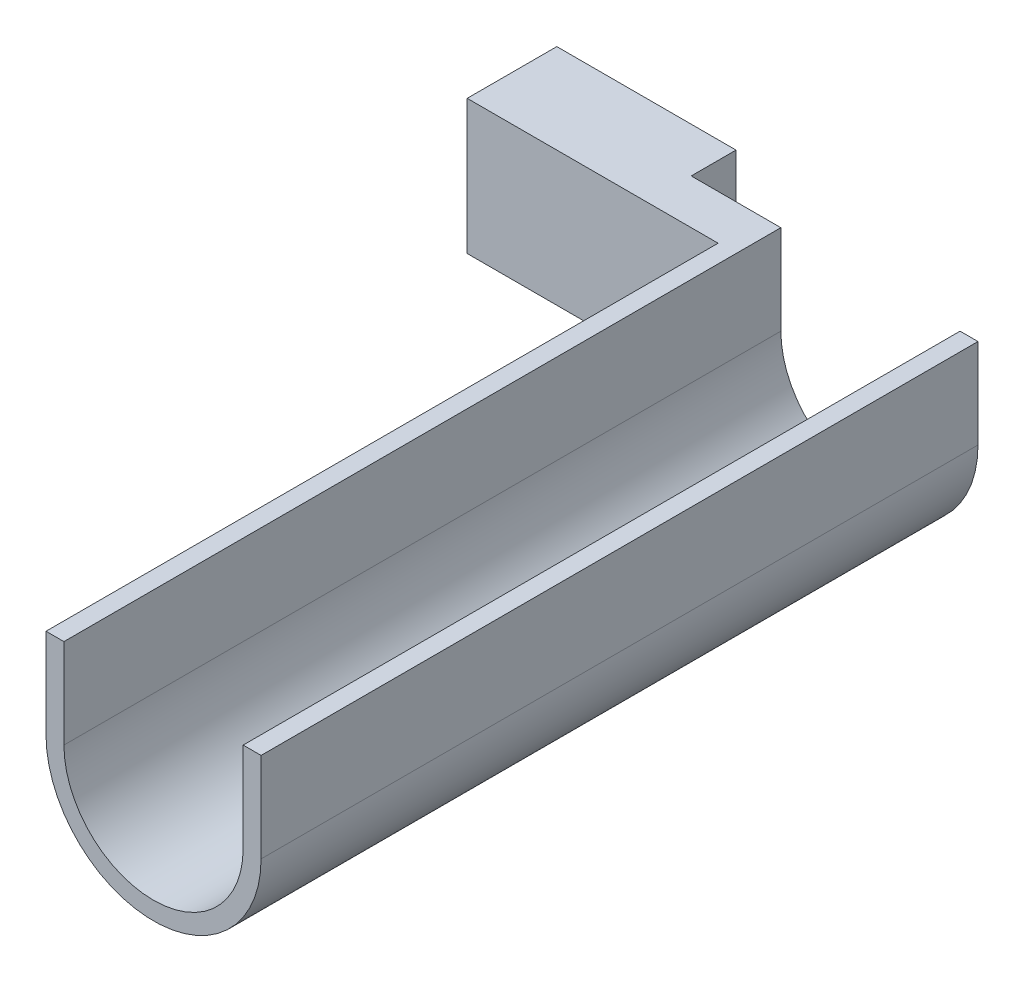
SolidWorks part; units mm, degrees
ref_plane "Front Plane" through (0, 0, 0) normal (0, 0, 1) x (1, 0, 0)
ref_plane "Top Plane" through (0, 0, 0) normal (0, 1, 0) x (1, 0, 0)
ref_plane "Right Plane" through (0, 0, 0) normal (1, 0, 0) x (0, 0, -1)
sketch "Sketch1" plane through (0, 0, 0) normal (0, 0, 1) x (1, 0, 0)
  line L0 (-10, 0) -> (-10, 10)
  line L2 (10, 10) -> (10, 0)
  line L6 (-12, 12) -> (12, 12) construction
  line L7 (-10, 10) -> (10, 10) construction
  line L8 (-12, 0) -> (-12, 12) construction
  line L9 (12, 12) -> (12, 0) construction
  line L10 (-12, 0) -> (-12, 10)
  line L11 (-12, 10) -> (-10, 10)
  line L12 (12, 0) -> (12, 10)
  line L13 (12, 10) -> (10, 10)
  arc A0 (-10, 0) -> (10, 0) centre (0, 0) ccw
  arc A1 (-12, 0) -> (12, 0) centre (0, 0) ccw
  dimension "D1" = 20
  dimension "D2" = 10
  dimension "D3" = 2
extrude "Boss-Extrude1" add sketch "Sketch1" along normal blind 80
sketch "Sketch2" plane through (0, 0, 0) normal (0, 0, -1) x (-1, 0, 0)
  line L1 (10, 10) -> (40, 10)
  line L2 (10, 10) -> (10, 0)
  line L3 (10, 0) -> (40, 0)
  line L4 (40, 10) -> (40, 0)
  dimension "D1" = 10
  dimension "D2" = 30
extrude "Boss-Extrude2" add sketch "Sketch2" against normal blind 5
sketch "Sketch3" plane through (0, 0, 0) normal (0, 0, -1) x (-1, 0, 0)
  line L0 (12, 0) -> (40, 0) construction
  line L1 (40, 10) -> (20, 10)
  line L2 (40, 10) -> (40, 0)
  line L3 (40, 0) -> (20, 0)
  line L4 (20, 10) -> (20, 0)
  dimension "D1" = 20
extrude "Boss-Extrude3" add sketch "Sketch3" along normal blind 5
sketch "Sketch4" plane through (0, 0, 0) normal (0, -1, 0) x (1, 0, 0)
  line L0 (-12, 0) -> (-12, 5)
  line L1 (-12, 5) -> (-40, 5)
  line L2 (-40, 5) -> (-40, -5)
  line L3 (-40, -5) -> (-20, -5)
  line L4 (-20, -5) -> (-20, 0)
  line L5 (-20, 0) -> (-12, 0)
extrude "Boss-Extrude4" add sketch "Sketch4" along normal blind 5
